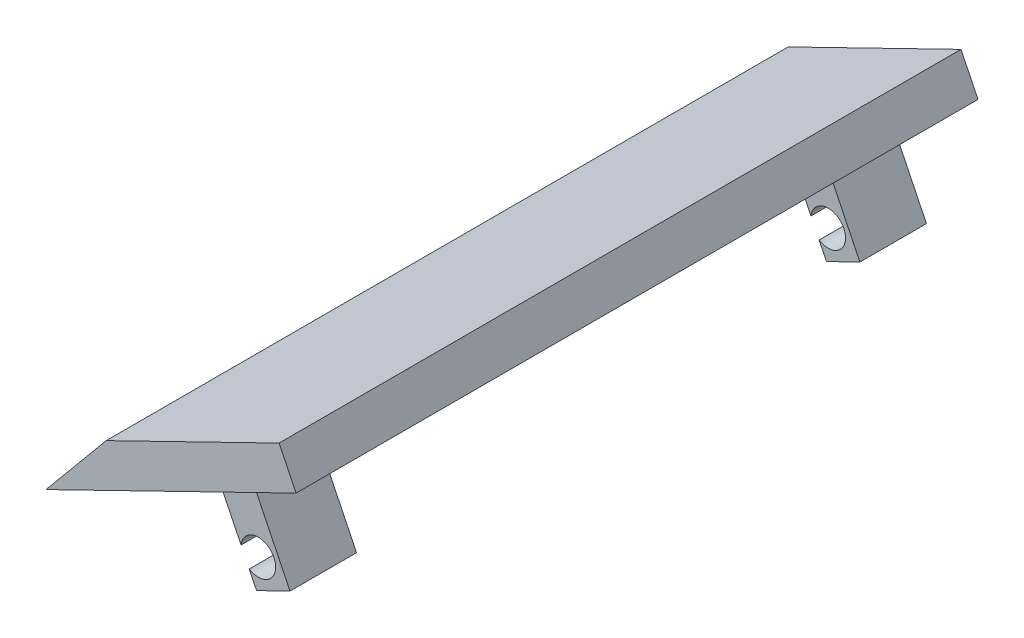
SolidWorks part; units mm, degrees
ref_plane "Front Plane" through (0, 0, 0) normal (0, 0, 1) x (1, 0, 0)
ref_plane "Top Plane" through (0, 0, 0) normal (0, 1, 0) x (1, 0, 0)
ref_plane "Right Plane" through (0, 0, 0) normal (1, 0, 0) x (0, 0, -1)
sketch "Sketch1" plane through (0, 0, 0) normal (0, 0, 1) x (1, 0, 0)
  line L5 (0, 0) -> (9.7172, 11.6957)
  line L12 (18.0788, 15.774) -> (37.5978, 25.2941)
  line L13 (0, 0) -> (40.3387, 19.6745)
  line L14 (37.5978, 25.2941) -> (40.3387, 19.6745)
  line L15 (9.7172, 11.6957) -> (18.0788, 15.774)
extrude "Boss-Extrude1" add sketch "Sketch1" along normal blind 110
sketch "Sketch3" plane through (0, 0, 0) normal (0.4384, -0.8988, 0) x (0.8988, 0.4384, 0)
  line L0 (44.8809, 55) -> (0, 55)
  line L1 (32.8809, 3.666) -> (26.8809, 3.666)
  line L2 (32.8809, 3.666) -> (32.8809, 14.4031)
  line L3 (32.8809, 14.4031) -> (26.8809, 14.4031)
  line L4 (26.8809, 3.666) -> (26.8809, 14.4031)
  line L5 (44.8809, 110) -> (44.8809, 0) construction
  line L6 (0, 110) -> (0, 0) construction
  line L7 (32.8809, 95.5969) -> (26.8809, 95.5969)
  line L8 (26.8809, 106.334) -> (26.8809, 95.5969)
  line L9 (32.8809, 106.334) -> (26.8809, 106.334)
  line L10 (32.8809, 106.334) -> (32.8809, 95.5969)
  point P14 (32.8809, 100.9654)
  dimension "D1" = 6
  dimension "D2" = 12
extrude "Boss-Extrude3" add sketch "Sketch3" along normal blind 14 contours L10 L9 L8 L7 | L4 L1 L2 L3
sketch "Sketch4" plane through (29.5532, 14.414, 0) normal (0.8988, 0.4384, 0) x (0, 0, -1)
  line L0 (-100.9654, 0) -> (-100.9654, -14) construction
  line L1 (-106.334, 0) -> (-95.5969, 0) construction
  line L2 (-106.334, -14) -> (-95.5969, -14) construction
  line L3 (-106.334, -7) -> (-95.5969, -7) construction
  line L4 (-106.334, -14) -> (-106.334, 0) construction
  line L5 (-95.5969, -14) -> (-95.5969, 0) construction
  circle A0 centre (-100.9654, -7) radius 1.4093
  point P15 (-100.9654, -7)
sketch "Sketch18" plane through (0, 0, 3.666) normal (0, 0, -1) x (-1, 0, 0)
  line L0 (-26.8568, 13.0989) -> (-33.3982, -2.8637) construction
  line L1 (-29.5532, 14.414) -> (-24.1604, 11.7838) construction
  line L2 (-35.6904, 1.8309) -> (-30.2976, -0.7993) construction
  circle A0 centre (-30.5807, 4.0117) radius 2.8
  dimension "D2" = 5.6
  dimension "D1" = 4.2
extrude "Cut-Extrude4" cut sketch "Sketch18" against normal through all
ref_plane "Plane1" through (0, 0, 55) normal (0, 0, 1) x (1, 0, 0)
